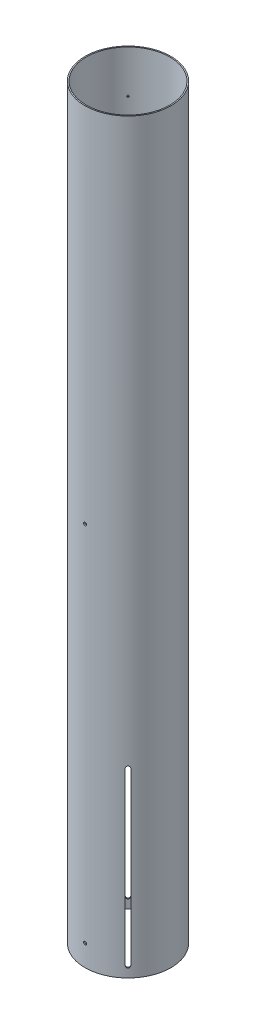
SolidWorks part; units mm, degrees
material "Wildman Fiberglass"
ref_plane "Front Plane" through (0, 0, 0) normal (0, 0, 1) x (1, 0, 0)
ref_plane "Top Plane" through (0, 0, 0) normal (0, 1, 0) x (1, 0, 0)
ref_plane "Right Plane" through (0, 0, 0) normal (1, 0, 0) x (0, 0, -1)
sketch "Sketch1" plane through (0, 0, 0) normal (0, 1, 0) x (1, 0, 0)
  circle A0 centre (0, 0) radius 49.657
  circle A1 centre (0, 0) radius 51.054
  dimension "D1" = 102.108
  dimension "D2" = 99.314
extrude "Boss-Extrude1" add sketch "Sketch1" along normal blind 887.984
extrude "Cut-Extrude1" cut sketch "Sketch2" against normal blind 152.4
sketch "Sketch2" plane through (14.5101, 1243.3556, -192.6465) normal (0.7071, 0, -0.7071) x (0, 1, 0)
  line L0 (-1230.6556, 128.3427) -> (-1027.4556, 128.3427)
  line L1 (-1027.4556, 123.5802) -> (-1230.6556, 123.5802)
  arc A0 (-1230.6556, 128.3427) -> (-1230.6556, 123.5802) centre (-1230.6556, 125.9615) ccw
  arc A1 (-1027.4556, 128.3427) -> (-1027.4556, 123.5802) centre (-1027.4556, 125.9615) cw
pattern_circular "CirPattern1" count 4 over 360 about axis through (0, 0, 0) along (0, 1, 0) of "Cut-Extrude1"
extrude "Cut-Extrude2" cut sketch "Sketch3" against normal blind 11.684
sketch "Sketch3" plane through (271.0916, 1243.3556, 52.6415) normal (0, 0, 1) x (-1, 0, 0)
  circle A0 centre (271.0916, 1217.9556) radius 1.7653
  circle A2 centre (271.0916, 786.1556) radius 1.7653
extrude "Cut-Extrude3" cut sketch "Sketch4" against normal blind 25.4
sketch "Sketch4" plane through (120.5803, 707.3886, -48.7382) normal (0.7071, 0, 0.7071) x (-0.7071, 0, 0.7071)
  line L0 (68.6723, -129.7954) -> (170.7803, -129.7954) construction
  circle A0 centre (119.7263, -129.7954) radius 1.0922
pattern_circular "CirPattern2" count 2 over 360 about axis through (0, 887.984, 0) along (0, -1, 0) of "Cut-Extrude3"
equation "\"Length\"=34.96"
equation "\"D1@Boss-Extrude1\"=\"Length\""
